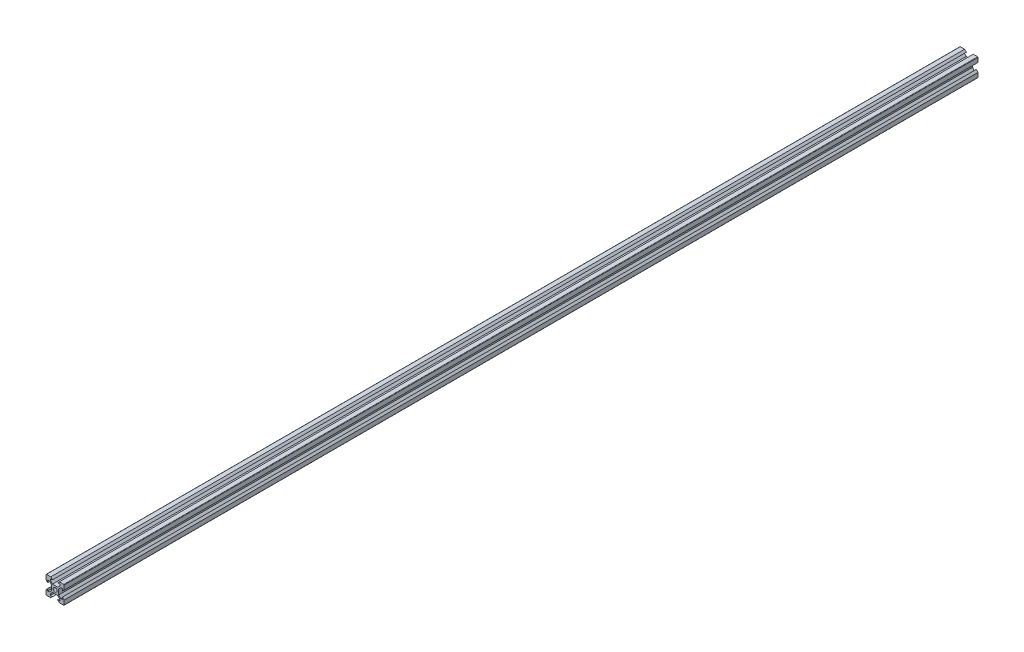
SolidWorks part; units mm, degrees
ref_plane "Front Plane" through (0, 0, 0) normal (0, 0, 1) x (1, 0, 0)
ref_plane "Top Plane" through (0, 0, 0) normal (0, 1, 0) x (1, 0, 0)
ref_plane "Right Plane" through (0, 0, 0) normal (1, 0, 0) x (0, 0, -1)
sketch "Sketch1" plane through (0, 0, 0) normal (0, 0, 1) x (1, 0, 0)
  line L0 (15.6876, 55.3211) -> (115.0437, 55.3211) construction
  line L1 (8.1, 5.225) -> (8.1, 2.85)
  line L2 (-9.5, 10) -> (-4.75, 10)
  line L3 (-10, 9.5) -> (-10, 4.75)
  line L4 (-9.5, -10) -> (-4.75, -10)
  line L5 (10, 9.5) -> (10, 4.75)
  line L6 (6.325, 5.225) -> (4, 2.9)
  line L7 (-8.1, -2.85) -> (-8.1, -5.225)
  line L8 (-2.9, 4) -> (2.9, 4)
  line L9 (-4, 2.9) -> (-4, -2.9)
  line L10 (-2.9, -4) -> (2.9, -4)
  line L11 (4, 2.9) -> (4, -2.9)
  line L12 (2.85, -8.1) -> (5.225, -8.1)
  line L13 (-5.225, -8.1) -> (-2.85, -8.1)
  line L14 (5.225, 6.325) -> (2.9, 4)
  line L17 (-10, 4.75) -> (-8.1, 2.85)
  line L20 (4.75, -10) -> (9.5, -10)
  line L22 (-10, -4.75) -> (-10, -9.5)
  line L23 (10, -4.75) -> (10, -9.5)
  line L24 (-10, -4.75) -> (-8.1, -2.85)
  line L25 (-4.75, -10) -> (-2.85, -8.1)
  line L26 (4.75, -10) -> (2.85, -8.1)
  line L27 (10, -4.75) -> (8.1, -2.85)
  line L28 (10, 4.75) -> (8.1, 2.85)
  line L29 (-4.75, 10) -> (-2.85, 8.1)
  line L30 (4.75, 10) -> (2.85, 8.1)
  line L31 (8.1, -2.85) -> (8.1, -5.225)
  line L32 (6.325, -5.225) -> (8.1, -5.225)
  line L33 (5.225, -6.325) -> (5.225, -8.1)
  line L34 (4.75, 10) -> (9.5, 10)
  line L35 (2.85, 8.1) -> (5.225, 8.1)
  line L36 (10, -10) -> (10.975, -10.975) construction
  line L37 (-5.225, 8.1) -> (-2.85, 8.1)
  line L38 (-8.1, -5.225) -> (-6.325, -5.225)
  line L39 (-5.225, 6.325) -> (-2.9, 4)
  line L40 (-8.1, 5.225) -> (-8.1, 2.85)
  line L41 (-5.225, -6.325) -> (-5.225, -8.1)
  line L42 (-6.325, 5.225) -> (-4, 2.9)
  line L46 (-8.1, 5.225) -> (-6.325, 5.225)
  line L47 (-5.225, 8.1) -> (-5.225, 6.325)
  line L52 (8.1, 5.225) -> (6.325, 5.225)
  line L53 (5.225, 8.1) -> (5.225, 6.325)
  line L63 (4, -2.9) -> (6.325, -5.225)
  line L66 (2.9, -4) -> (5.225, -6.325)
  line L67 (-2.9, -4) -> (-5.225, -6.325)
  line L70 (-4, -2.9) -> (-6.325, -5.225)
  arc A0 (-9.5, -10) -> (-10, -9.5) centre (-9.5, -9.5) cw
  arc A1 (9.5, -10) -> (10, -9.5) centre (9.5, -9.5) ccw
  arc A2 (10, 9.5) -> (9.5, 10) centre (9.5, 9.5) ccw
  arc A3 (-9.5, 10) -> (-10, 9.5) centre (-9.5, 9.5) ccw
  circle A4 centre (0, 0) radius 2.125
  point P2 (0, 0)
  point P8 (0, 0)
  point P14 (-10, -10)
  point P20 (0, 0)
  point P49 (10, 10)
  point P52 (-10, 10)
  dimension "D3" = 0.5
  dimension "D4" = 4.25
  dimension "D1" = 20
  dimension "D2" = 20
  dimension "D13" = 5.25
  dimension "D14" = 5.25
  dimension "D15" = 90
  dimension "D16" = 5.25
  dimension "D17" = 5.25
  dimension "D18" = 5.25
  dimension "D19" = 5.25
  dimension "D20" = 5.25
  dimension "D21" = 5.25
  dimension "D22" = 90
  dimension "D23" = 90
  dimension "D24" = 90
  dimension "D25" = 2.85
  dimension "D26" = 2.85
  dimension "D27" = 2.85
  dimension "D28" = 2.85
extrude "Boss-Extrude1" add sketch "Sketch1" along normal blind 1007.5
